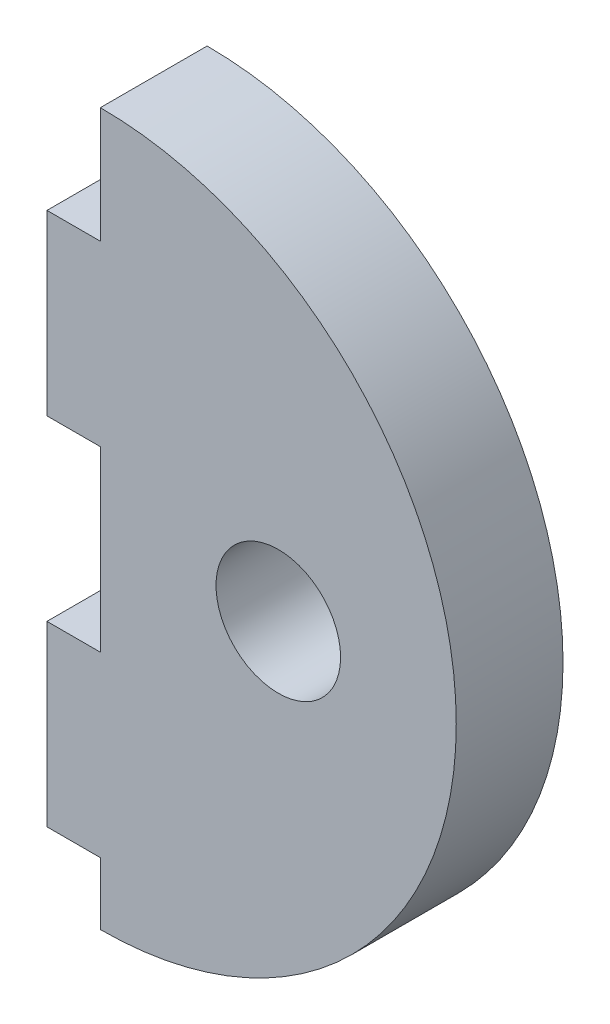
SolidWorks part; units mm, degrees
ref_plane "Front Plane" through (0, 0, 0) normal (0, 0, 1) x (1, 0, 0)
ref_plane "Top Plane" through (0, 0, 0) normal (0, 1, 0) x (1, 0, 0)
ref_plane "Right Plane" through (0, 0, 0) normal (1, 0, 0) x (0, 0, -1)
sketch "Sketch1" plane through (0, 0, 0) normal (0, 0, 1) x (1, 0, 0)
  line L0 (0, 0) -> (0, 10)
  line L1 (0, 10) -> (3, 10)
  line L2 (3, 10) -> (3, 20)
  line L3 (3, 20) -> (0, 20)
  line L4 (0, 20) -> (0, 30)
  line L5 (0, 30) -> (3, 30)
  line L6 (3, 30) -> (3, 36.5)
  line L7 (0, 0) -> (3, 0)
  line L8 (3, 0) -> (3, -3.5)
  arc A0 (3, 36.5) -> (3, -3.5) centre (3, 16.5) cw
  circle A1 centre (13, 16.5) radius 3.5
  point P10 (0, 0)
  dimension "D2" = 3
  dimension "D5" = 7
  dimension "D6" = 10
  dimension "D4" = 20
  dimension "D8" = 20
  dimension "D1" = 30
  dimension "D3" = 40
  dimension "D7" = 10
  dimension "D9" = 3.5
extrude "Boss-Extrude1" add sketch "Sketch1" along normal blind 6
